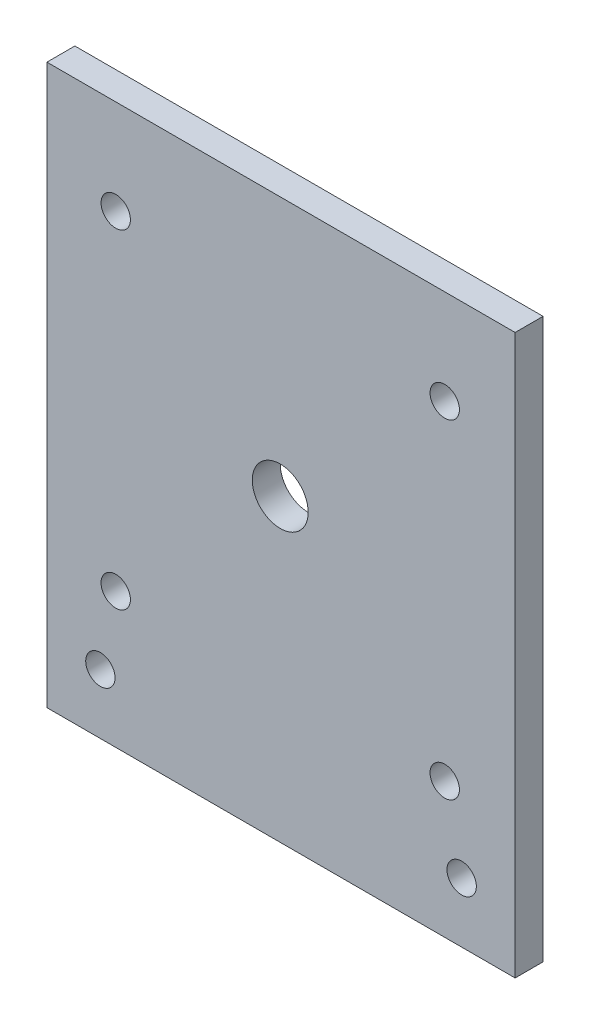
SolidWorks part; units mm, degrees
ref_plane "Plan de face" through (0, 0, 0) normal (0, 0, 1) x (1, 0, 0)
ref_plane "Plan de dessus" through (0, 0, 0) normal (0, 1, 0) x (1, 0, 0)
ref_plane "Plan de droite" through (0, 0, 0) normal (1, 0, 0) x (0, 0, -1)
sketch "Esquisse1" plane through (0, 0, 0) normal (0, 0, 1) x (1, 0, 0)
  line L1 (32.5, -40) -> (-32.5, -40)
  line L2 (32.5, -40) -> (32.5, 40)
  line L3 (32.5, 40) -> (-32.5, 40)
  line L4 (-32.5, -40) -> (-32.5, 40)
  line L5 (32.5, -40) -> (-32.5, 40) construction
  line L6 (32.5, 40) -> (-32.5, -40) construction
  point P0 (0, 0)
  dimension "D1" = 65
  dimension "D2" = 80
extrude "Boss.-Extru.1" add sketch "Esquisse1" along normal blind 4
sketch "Esquisse2" plane through (0, 0, 0) normal (0, 0, -1) x (-1, 0, 0)
  line L0 (0, 0) -> (0, -40) construction
  line L1 (32.5, -40) -> (-32.5, -40) construction
  circle A0 centre (25.85, -31.439) radius 2.1
  circle A1 centre (-25.85, -31.439) radius 2.1
  dimension "D1" = 4.2
  dimension "D2" = 25.85
  dimension "D3" = 8.561
extrude "Enlèv. mat.-Extru.1" cut sketch "Esquisse2" against normal through all
sketch "Esquisse3" plane through (0, 0, 4) normal (0, 0, 1) x (1, 0, 0)
  line L0 (-32.5, 40) -> (-32.5, -40) construction
  line L1 (23.4266, -20.64) -> (-23.6534, -20.64) construction
  line L2 (23.4266, -20.64) -> (23.4266, 26.44) construction
  line L3 (23.4266, 26.44) -> (-23.6534, 26.44) construction
  line L4 (-23.6534, -20.64) -> (-23.6534, 26.44) construction
  line L5 (32.5, 40) -> (-32.5, 40) construction
  line L6 (23.4266, -20.64) -> (-23.6534, 26.44) construction
  circle A0 centre (-23.6534, -20.64) radius 2.1
  circle A1 centre (23.4266, -20.64) radius 2.1
  circle A2 centre (23.4266, 26.44) radius 2.1
  circle A3 centre (-23.6534, 26.44) radius 2.1
  circle A4 centre (-0.1134, 2.9) radius 4
  point P0 (-0.1134, 2.9)
  dimension "D1" = 4.2
  dimension "D2" = 8
  dimension "D3" = 47.08
  dimension "D4" = 8.8466
  dimension "D5" = 13.56
extrude "Enlèv. mat.-Extru.2" cut sketch "Esquisse3" against normal through all
sketch "Esquisse4" plane through (0, 0, 0) normal (0, 0, -1) x (-1, 0, 0)
  line L0 (-32.5, 40) -> (32.5, 40) construction
  line L1 (32.5, -40) -> (33.5, -40)
  line L2 (32.5, -40) -> (32.5, 40)
  line L3 (32.5, 40) -> (33.5, 40)
  line L4 (33.5, -40) -> (33.5, 40)
  line L5 (0, -40) -> (0, 40) construction
  line L6 (32.5, -40) -> (-32.5, -40) construction
  line L7 (-33.5, -40) -> (-33.5, 40)
  line L8 (-32.5, 40) -> (-33.5, 40)
  line L9 (-32.5, -40) -> (-32.5, 40)
  line L10 (-32.5, -40) -> (-33.5, -40)
  dimension "D1" = 1
extrude "Boss.-Extru.2" add sketch "Esquisse4" against normal blind 4
